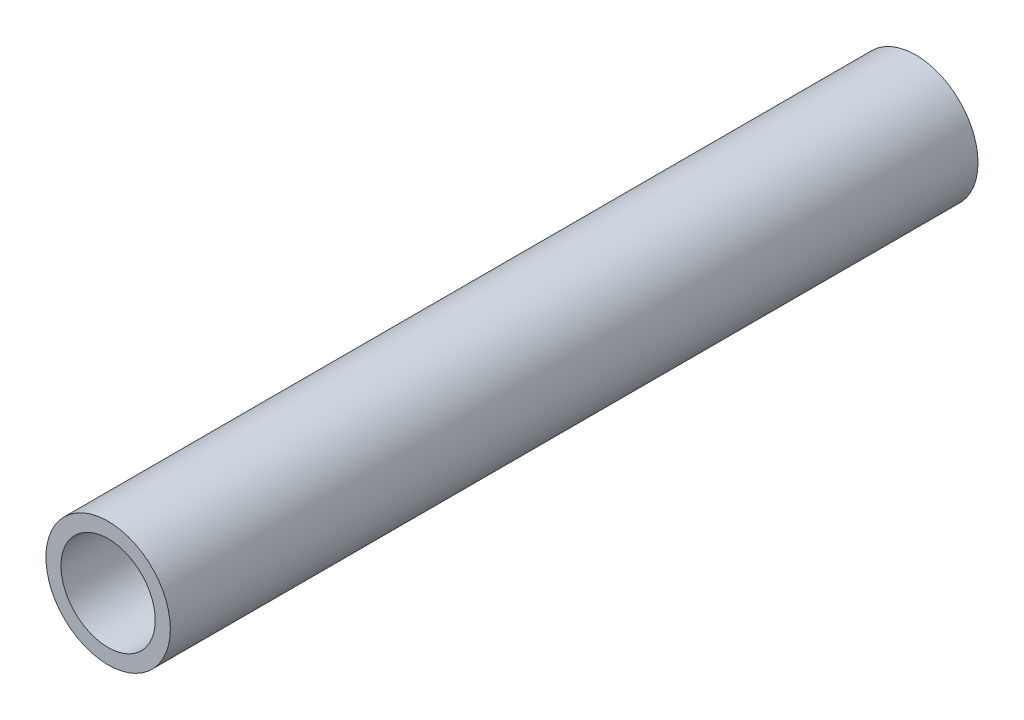
SolidWorks part; units mm, degrees
material "AISI 304"
ref_plane "前基準面" through (0, 0, 0) normal (0, 0, 1) x (1, 0, 0)
ref_plane "上基準面" through (0, 0, 0) normal (0, 1, 0) x (1, 0, 0)
ref_plane "右基準面" through (0, 0, 0) normal (1, 0, 0) x (0, 0, -1)
sketch "Sketch1" plane through (0, 0, 0) normal (0, 0, 1) x (1, 0, 0)
  circle A0 centre (0, 0) radius 14.6685
  circle A1 centre (0, 0) radius 11.1125
  dimension "D1" = 22.225
  dimension "D2" = 29.337
extrude "Boss-Extrude1" add sketch "Sketch1" along normal mid plane 190.4
